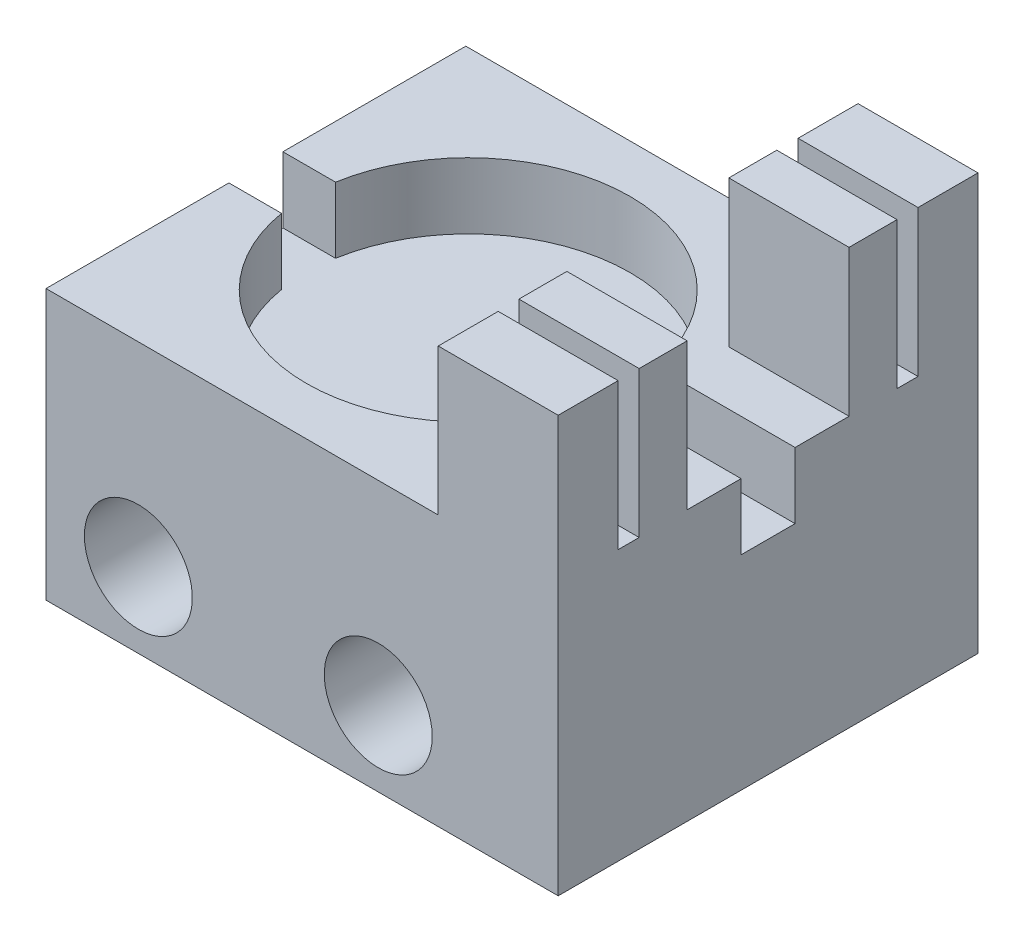
SolidWorks part; units mm, degrees
ref_plane "Front Plane" through (0, 0, 0) normal (0, 0, 1) x (1, 0, 0)
ref_plane "Top Plane" through (0, 0, 0) normal (0, 1, 0) x (1, 0, 0)
ref_plane "Right Plane" through (0, 0, 0) normal (1, 0, 0) x (0, 0, -1)
sketch "Sketch1" plane through (0, 0, 0) normal (0, 0, 1) x (1, 0, 0)
  line L1 (-25, -11.25) -> (25, -11.25)
  line L2 (-25, -11.25) -> (-25, 11.25)
  line L3 (-25, 11.25) -> (25, 11.25)
  line L4 (25, -11.25) -> (25, 11.25)
  line L5 (-25, -11.25) -> (25, 11.25) construction
  line L6 (-25, 11.25) -> (25, -11.25) construction
  point P0 (0, 0)
  dimension "D1" = 50
  dimension "D2" = 22.5
extrude "Boss-Extrude1" add sketch "Sketch1" along normal blind 35
sketch "Sketch2" plane through (0, 0, 35) normal (0, 0, 1) x (1, 0, 0)
  line L0 (25, 0) -> (-25, 0) construction
  line L1 (25, -11.25) -> (25, 11.25) construction
  line L2 (-25, 11.25) -> (-25, -11.25) construction
  line L3 (0, 11.25) -> (0, -11.25) construction
  line L4 (25, 11.25) -> (-25, 11.25) construction
  line L5 (-25, -11.25) -> (25, -11.25) construction
  circle A0 centre (10, -5) radius 4.5
  circle A1 centre (-10, -5) radius 4.5
  dimension "D2" = 9
  dimension "D1" = 10
  dimension "D3" = 6.25
extrude "Cut-Extrude1" cut sketch "Sketch2" against normal blind 35
sketch "Sketch3" plane through (0, 11.25, 0) normal (0, 1, 0) x (1, 0, 0)
  line L0 (25, 0) -> (3.2143, -15.25) construction
  line L1 (-25, -35) -> (25, -35) construction
  line L2 (25, -35) -> (0, -17.5) construction
  line L3 (-25, -35) -> (-25, 0) construction
  line L4 (25, -19.75) -> (13.3112, -19.75)
  line L5 (25, -19.75) -> (25, -15.25)
  line L6 (25, -15.25) -> (13.3112, -15.25)
  line L7 (-25, -19.75) -> (-25, -15.25)
  line L8 (-13.3112, -15.25) -> (-25, -15.25)
  line L9 (-13.3112, -19.75) -> (-25, -19.75)
  line L11 (-3.2143, -15.25) -> (-25, 0) construction
  line L12 (0, -17.5) -> (-25, -35) construction
  arc A0 (-13.3112, -19.75) -> (13.3112, -19.75) centre (0, -17.5) ccw
  arc A1 (13.3112, -15.25) -> (-13.3112, -15.25) centre (0, -17.5) ccw
  dimension "D1" = 27
  dimension "D2" = 4.5
extrude "Cut-Extrude2" cut sketch "Sketch3" against normal blind 5.5
sketch "Sketch4" plane through (0, 11.25, 0) normal (0, 1, 0) x (1, 0, 0)
  line L0 (25, -15.25) -> (25, 0) construction
  line L1 (25, 0) -> (15, 0)
  line L2 (25, 0) -> (25, -5)
  line L3 (25, -5) -> (15, -5)
  line L4 (15, 0) -> (15, -5)
  line L5 (25, -6.75) -> (14.976, -6.75)
  line L6 (25, -6.75) -> (25, -10.75)
  line L7 (25, -10.75) -> (14.976, -10.75)
  line L8 (14.976, -6.75) -> (14.976, -10.75)
  line L9 (25, -17.5) -> (-25, -17.5) construction
  line L10 (25, -19.75) -> (25, -15.25) construction
  line L11 (-25, -15.25) -> (-25, -19.75) construction
  line L12 (25, -24.25) -> (14.976, -24.25)
  line L13 (14.976, -28.25) -> (14.976, -24.25)
  line L14 (25, -28.25) -> (14.976, -28.25)
  line L15 (25, -28.25) -> (25, -24.25)
  line L16 (25, -30) -> (15, -30)
  line L17 (15, -35) -> (15, -30)
  line L18 (25, -35) -> (15, -35)
  line L19 (25, -35) -> (25, -30)
  dimension "D1" = 10
  dimension "D2" = 1.75
  dimension "D3" = 4
  dimension "D4" = 5
extrude "Boss-Extrude2" add sketch "Sketch4" along normal blind 12.2
sketch "Sketch5" plane through (0, 0, 0) normal (0, 0, -1) x (-1, 0, 0)
  line L0 (25, -11.25) -> (-25, -11.25) construction
  line L1 (25, 11.25) -> (17.7, 11.25)
  line L2 (25, 11.25) -> (25, -11.25)
  line L3 (25, -11.25) -> (17.7, -11.25)
  line L4 (17.7, 11.25) -> (17.7, -11.25)
  dimension "D1" = 7.3
extrude "Cut-Extrude3" cut sketch "Sketch5" against normal through all
